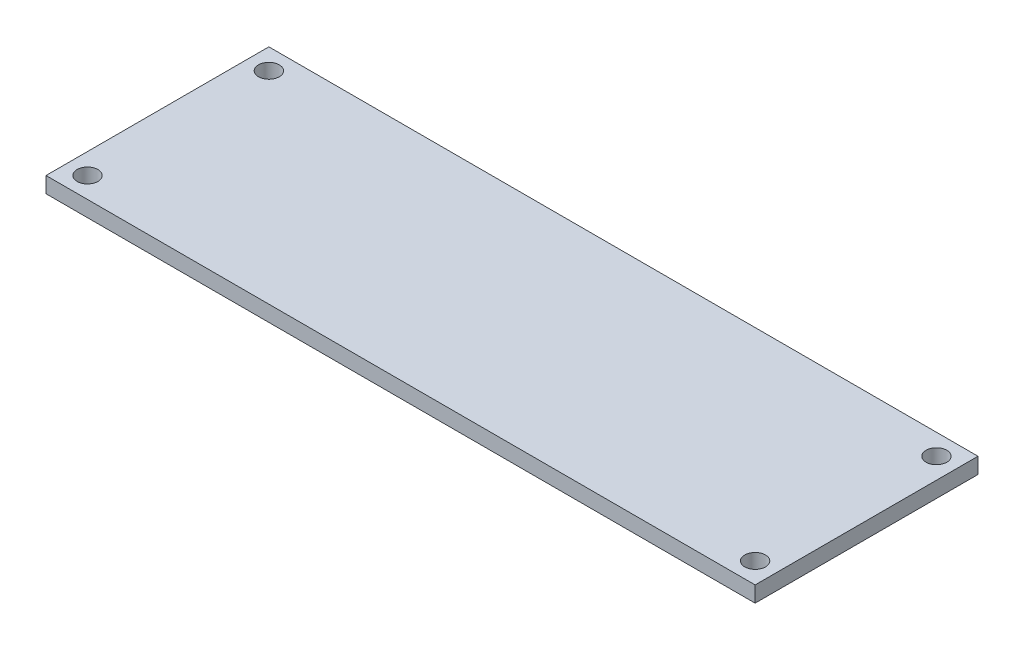
SolidWorks part; units mm, degrees
ref_plane "Front Plane" through (0, 0, 0) normal (0, 0, 1) x (1, 0, 0)
ref_plane "Top Plane" through (0, 0, 0) normal (0, 1, 0) x (1, 0, 0)
ref_plane "Right Plane" through (0, 0, 0) normal (1, 0, 0) x (0, 0, -1)
sketch "Sketch1" plane through (0, 0, 0) normal (0, 1, 0) x (1, 0, 0)
  line L1 (-71.12, -22.352) -> (71.12, -22.352)
  line L2 (-71.12, -22.352) -> (-71.12, 22.352)
  line L3 (-71.12, 22.352) -> (71.12, 22.352)
  line L4 (71.12, -22.352) -> (71.12, 22.352)
  line L5 (-71.12, -22.352) -> (71.12, 22.352) construction
  line L6 (-71.12, 22.352) -> (71.12, -22.352) construction
  point P0 (0, 0)
  dimension "D1" = 142.24
  dimension "D2" = 44.704
extrude "Boss-Extrude1" add sketch "Sketch1" along normal blind 3.175
sketch "Sketch2" plane through (0, 3.175, 0) normal (0, 1, 0) x (1, 0, 0)
  line L0 (-71.12, 22.352) -> (-71.12, -22.352) construction
  line L1 (-64.77, -16.002) -> (64.77, -16.002) construction
  line L2 (-64.77, -16.002) -> (-64.77, 16.002) construction
  line L3 (-64.77, 16.002) -> (64.77, 16.002) construction
  line L4 (64.77, -16.002) -> (64.77, 16.002) construction
  line L5 (-64.77, -16.002) -> (64.77, 16.002) construction
  line L6 (-64.77, 16.002) -> (64.77, -16.002) construction
  line L7 (71.12, 22.352) -> (-71.12, 22.352) construction
  line L8 (0, 22.352) -> (0, -49977.648) construction
  line L9 (-71.12, -22.352) -> (71.12, -22.352) construction
  line L10 (-71.12, 0) -> (49928.88, 0) construction
  line L11 (71.12, -22.352) -> (71.12, 22.352) construction
  circle A0 centre (-66.9544, 18.1864) radius 2.0828
  circle A1 centre (-66.9544, -18.1864) radius 2.0828
  circle A2 centre (66.9544, 18.1864) radius 2.0828
  circle A3 centre (66.9544, -18.1864) radius 2.0828
  point P0 (0, 0)
  point P15 (0, 22.352)
  point P18 (0, -22.352)
  point P20 (-71.12, 0)
  point P23 (71.12, 0)
  dimension "D3" = 4.1656
  dimension "D1" = 32.004
  dimension "D2" = 129.54
  dimension "D4" = 4.1656
  dimension "D5" = 4.1656
extrude "Cut-Extrude1" cut sketch "Sketch2" against normal through all
